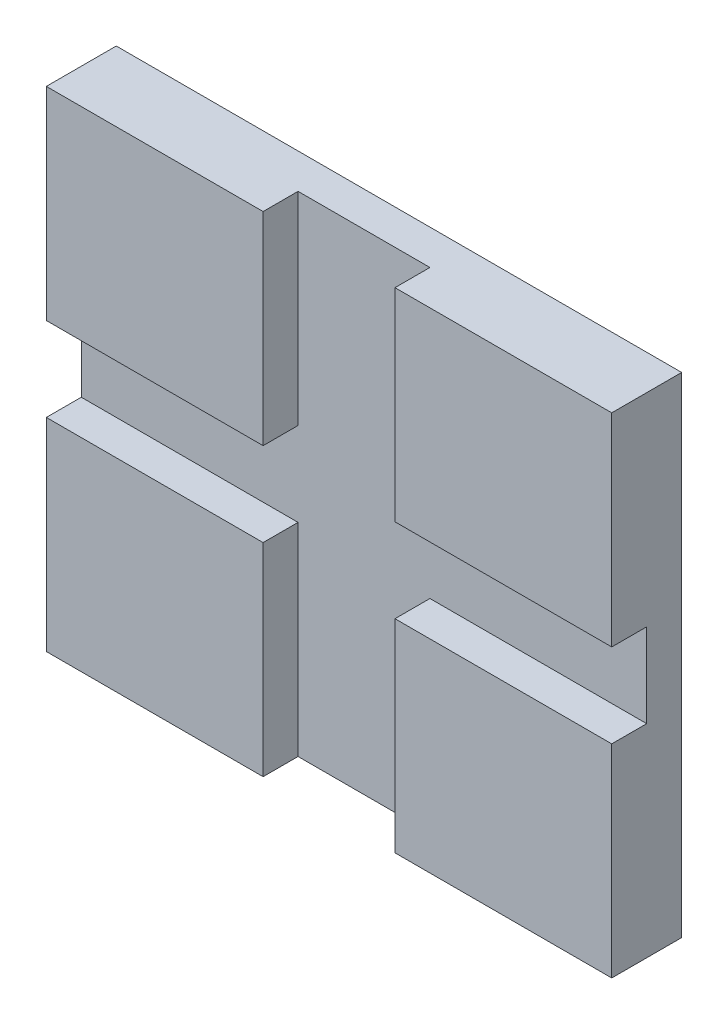
SolidWorks part; units mm, degrees
ref_plane "Top Plane" through (0, 0, 0) normal (0, 0, 1) x (1, 0, 0)
ref_plane "Right Plane" through (0, 0, 0) normal (0, 1, 0) x (1, 0, 0)
ref_plane "Front Plane" through (0, 0, 0) normal (1, 0, 0) x (0, 0, -1)
sketch "Sketch1" plane through (0, 0, 0) normal (0, 0, 1) x (1, 0, 0)
  line L1 (-80.86, 0) -> (0, 0)
  line L2 (-80.86, 0) -> (-80.86, -70)
  line L3 (-80.86, -70) -> (0, -70)
  line L4 (0, 0) -> (0, -70)
  point P4 (0, 0)
  dimension "D1" = 70
  dimension "D2" = 80.86
extrude "Boss-Extrude1" add sketch "Sketch1" along normal blind 10
sketch "Sketch2" plane through (0, 0, 10) normal (0, 0, 1) x (1, 0, 0)
  line L1 (-80.86, -70) -> (-18.86, -70)
  line L2 (-80.86, -70) -> (-80.86, -12)
  line L3 (-80.86, -12) -> (-18.86, -12)
  line L4 (-18.86, -70) -> (-18.86, -12)
  dimension "D1" = 58
  dimension "D2" = 62
extrude "Boss-Extrude2" add sketch "Sketch2" along normal blind 10
mirror "Mirror1" about plane through (0, 0, 10) normal (-1, 0, 0) of bodies 103
mirror "Mirror2" about plane through (-80.86, 0, 10) normal (0, -1, 0) of bodies 104
